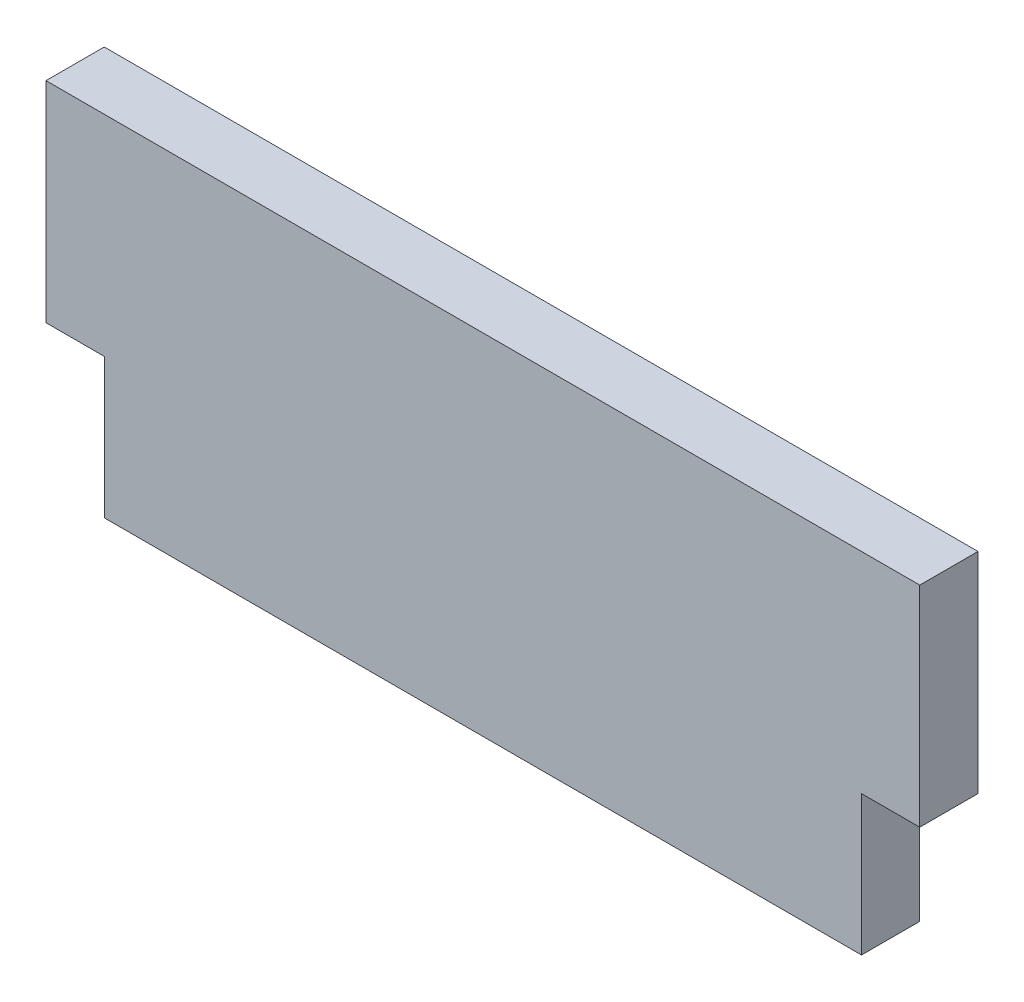
SolidWorks part; units mm, degrees
ref_plane "Front" through (0, 0, 0) normal (0, 0, 1) x (1, 0, 0)
ref_plane "Top" through (0, 0, 0) normal (0, 1, 0) x (1, 0, 0)
ref_plane "Right" through (0, 0, 0) normal (1, 0, 0) x (0, 0, -1)
sketch "Skizze1" plane through (0, 0, 0) normal (0, 0, 1) x (1, 0, 0)
  line L1 (0, 0) -> (75, 0)
  line L2 (0, 0) -> (0, 30)
  line L3 (0, 30) -> (75, 30)
  line L4 (75, 0) -> (75, 30)
  dimension "D1" = 30
  dimension "D2" = 75
extrude "Aufsatz-Linear austragen1" add sketch "Skizze1" along normal blind 5
sketch "Skizze2" plane through (0, 0, 5) normal (0, 0, 1) x (1, 0, 0)
  line L0 (37.5, 30) -> (37.5, 0) construction
  line L1 (0, 0) -> (5, 0)
  line L2 (0, 0) -> (0, 12)
  line L3 (0, 12) -> (5, 12)
  line L4 (5, 0) -> (5, 12)
  line L5 (75, 30) -> (0, 30) construction
  line L6 (0, 0) -> (75, 0) construction
  line L7 (70, 0) -> (70, 12)
  line L8 (75, 12) -> (70, 12)
  line L9 (75, 0) -> (75, 12)
  line L10 (75, 0) -> (70, 0)
  point P9 (37.5, 0)
  dimension "D1" = 5
  dimension "D2" = 12
extrude "Schnitt-Linear austragen1" cut sketch "Skizze2" against normal through all
